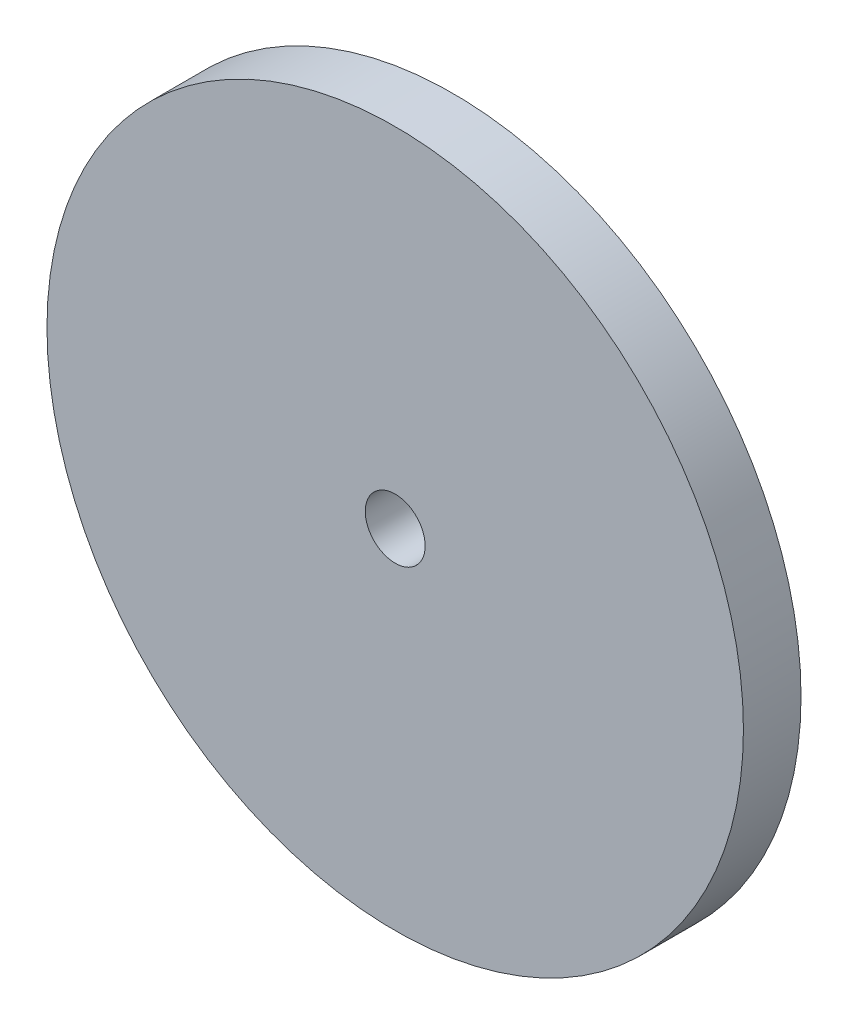
SolidWorks part; units mm, degrees
material "E-Glass Fiber"
ref_plane "Front Plane" through (0, 0, 0) normal (0, 0, 1) x (1, 0, 0)
ref_plane "Top Plane" through (0, 0, 0) normal (0, 1, 0) x (1, 0, 0)
ref_plane "Right Plane" through (0, 0, 0) normal (1, 0, 0) x (0, 0, -1)
sketch "Sketch1" plane through (0, 0, 0) normal (0, 0, 1) x (1, 0, 0)
  circle A0 centre (0, 0) radius 19.2
  circle A1 centre (0, 0) radius 1.651 construction
  circle A2 centre (0, 0) radius 1.651
  arc A7 (7.62, 3.0611) -> (7.62, -9.4111) centre (7.62, -3.175) ccw
  arc A8 (7.62, -9.4111) -> (7.62, 3.0611) centre (7.62, -3.175) ccw
  arc A9 (7.62, 3.0611) -> (7.62, -9.4111) centre (7.62, -3.175) ccw
  arc A10 (7.62, -9.4111) -> (7.62, 3.0611) centre (7.62, -3.175) ccw
  dimension "D1" = 0.9525
extrude "Boss-Extrude1" add sketch "Sketch1" along normal blind 3.175
sketch "Sketch2" plane through (0, 0, 0) normal (0, 0, -1) x (-1, 0, 0)
  circle A0 centre (-7.62, -3.175) radius 6.2361 construction
  circle A1 centre (-7.62, -3.175) radius 6.2361
extrude "Boss-Extrude2" add sketch "Sketch2" against normal up to surface (3.175 mm away) up to face at (1.651, 0, 3.175)
